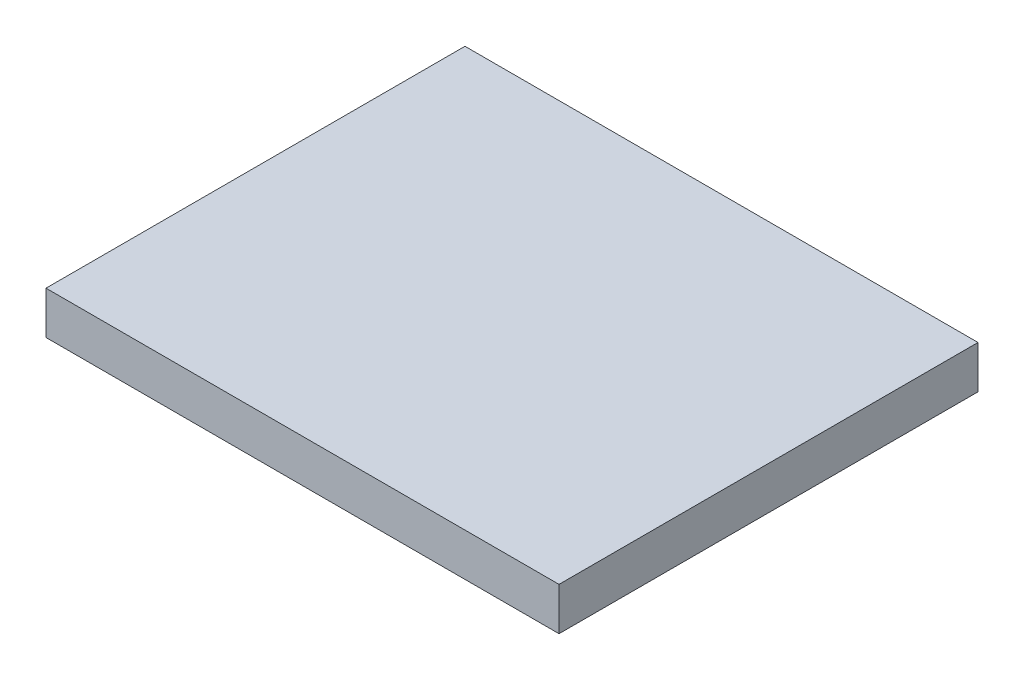
SolidWorks part; units mm, degrees
material "6063-T6"
ref_plane "Front Plane" through (0, 0, 0) normal (0, 0, 1) x (1, 0, 0)
ref_plane "Top Plane" through (0, 0, 0) normal (0, 1, 0) x (1, 0, 0)
ref_plane "Right Plane" through (0, 0, 0) normal (1, 0, 0) x (0, 0, -1)
sketch "Sketch1" plane through (0, 0, 0) normal (0, 1, 0) x (1, 0, 0)
  line L5 (-60, 49) -> (60, 49)
  line L6 (-60, 49) -> (-60, -49)
  line L7 (-60, -49) -> (60, -49)
  line L8 (60, 49) -> (60, -49)
  line L9 (-60, 49) -> (60, -49) construction
  line L10 (-60, -49) -> (60, 49) construction
  point P0 (0, 0)
extrude "Boss-Extrude1" add sketch "Sketch1" along normal blind 10
